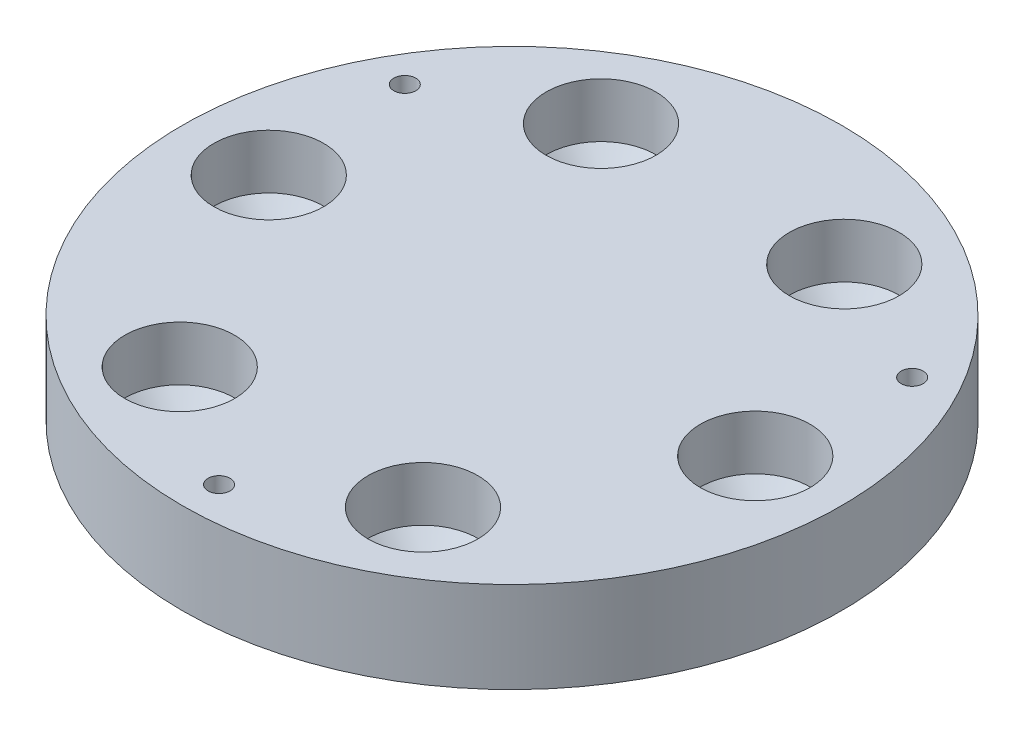
SolidWorks part; units mm, degrees
ref_plane "Front Plane" through (0, 0, 0) normal (0, 0, 1) x (1, 0, 0)
ref_plane "Top Plane" through (0, 0, 0) normal (0, 1, 0) x (1, 0, 0)
ref_plane "Right Plane" through (0, 0, 0) normal (1, 0, 0) x (0, 0, -1)
sketch "Sketch1" plane through (0, 0, 0) normal (0, 1, 0) x (1, 0, 0)
  circle A0 centre (0, 0) radius 45
  dimension "D1" = 90
extrude "Boss-Extrude1" add sketch "Sketch1" against normal blind 2 and the other way blind 10.4254 contours A0
sketch "Sketch2" plane through (0, 10.4254, 0) normal (0, 1, 0) x (1, 0, 0)
  circle A0 centre (0, 0) radius 33.2139
  point P3 (16.607, 28.7641)
  point P4 (-16.607, 28.7641)
  point P5 (-33.2139, 0)
  point P6 (-16.607, -28.7641)
  point P7 (16.607, -28.7641)
  point P8 (33.2139, 0)
hole_wizard "Ø8.0mm Dowel Hole1" positions "Sketch3" profile "Sketch4" hole size "Ø8.0" standard "ANSI Metric"
sketch "Sketch3" plane through (0, 10.4254, 0) normal (0, 1, 0) x (1, 0, 0)
  point P0 (-16.607, 28.7641)
  point P3 (-16.607, -28.7641)
  point P6 (33.2139, 0)
  point P9 (16.607, 28.7641)
  point P12 (16.607, -28.7641)
  point P15 (-33.2139, 0)
sketch "Sketch4" plane through (-16.607, 10.4254, -28.7641) normal (1, 0, 0) x (0, 0, 1)
  line L0 (0, 0) -> (0, 14.9254)
  line L1 (0, 14.9254) -> (7.5, 7.4254)
  line L2 (7.5, 7.4254) -> (7.5, 0)
  line L5 (7.5, 0) -> (0, 0)
  line L10 (0, 14.9254) -> (-7.5, 7.4254) construction
  line L11 (0, -6.35) -> (0, 107.95) construction
  dimension "Hole Dia." = 15
  dimension "Hole Depth" = 7.4254
  dimension "Drill Angle" = 90
sketch "Sketch10" plane through (0, 10.4254, 0) normal (0, 1, 0) x (1, 0, 0)
  circle A0 centre (0, 0) radius 40
  point P3 (-34.641, 20)
  point P4 (0, -40)
  point P5 (34.641, 20)
hole_wizard "Ø3.0 (3) Diameter Hole1" positions "Sketch11" profile "Sketch12" hole size "Ø3.0" standard "ANSI Metric" end condition through all
sketch "Sketch11" plane through (0, 10.4254, 0) normal (0, 1, 0) x (1, 0, 0)
  point P0 (-34.641, 20)
  point P3 (0, -40)
  point P6 (34.641, 20)
sketch "Sketch12" plane through (-34.641, 10.4254, -20) normal (1, 0, 0) x (0, 0, 1)
  line L0 (0, 0) -> (0, 12.4254)
  line L1 (0, 12.4254) -> (1.5, 12.4254)
  line L2 (1.5, 12.4254) -> (1.5, 0)
  line L5 (1.5, 0) -> (0, 0)
  line L11 (0, -6.35) -> (0, 107.95) construction
  dimension "Thru Hole Dia." = 3
  dimension "Thru Hole Depth" = 12.4254
